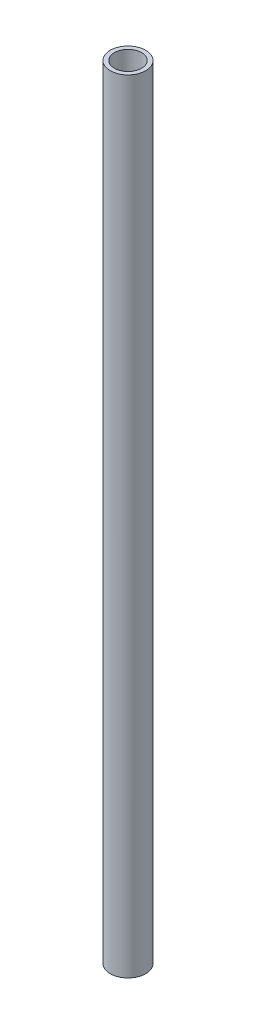
SolidWorks part; units mm, degrees
material "AISI 4130 Steel, annealed at 865C"
ref_plane "X-Y Datum" through (0, 0, 0) normal (0, 0, 1) x (1, 0, 0)
ref_plane "X-Z Datum" through (0, 0, 0) normal (0, 1, 0) x (1, 0, 0)
ref_plane "Y-Z Datum" through (0, 0, 0) normal (1, 0, 0) x (0, 0, -1)
sketch "Sketch1" plane through (0, 0, 0) normal (0, 1, 0) x (1, 0, 0)
  circle A0 centre (0, 0) radius 6.35
  circle A1 centre (0, 0) radius 4.8768
  dimension "D1" = 1.4732
  dimension "D2" = 12.7
extrude "Boss-Extrude1" add sketch "Sketch1" along normal up to surface (280.1715 mm away) from surface
